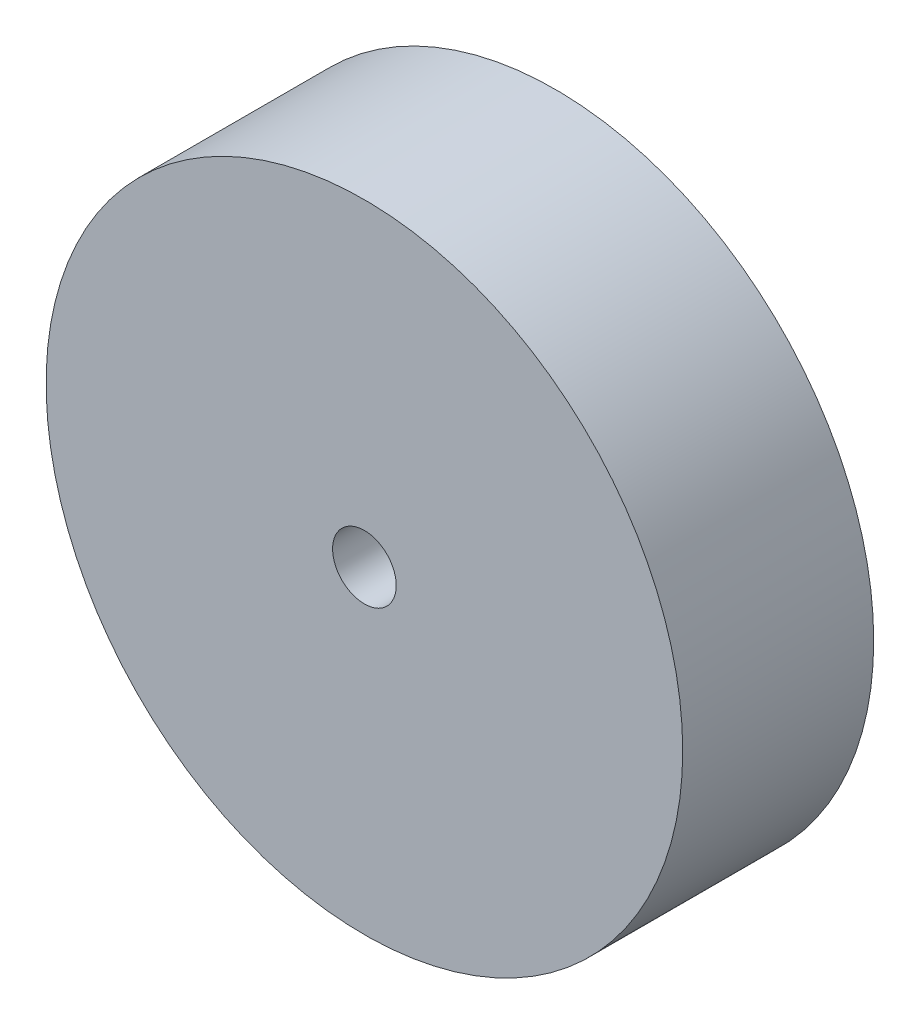
SolidWorks part; units mm, degrees
ref_plane "Front Plane" through (0, 0, 0) normal (0, 0, 1) x (1, 0, 0)
ref_plane "Top Plane" through (0, 0, 0) normal (0, 1, 0) x (1, 0, 0)
ref_plane "Right Plane" through (0, 0, 0) normal (1, 0, 0) x (0, 0, -1)
sketch "Sketch1" plane through (0, 0, 0) normal (0, 0, 1) x (1, 0, 0)
  circle A0 centre (0, 0) radius 25
  circle A1 centre (0, 0) radius 2.5
  dimension "D1" = 50
  dimension "D2" = 5
extrude "Boss-Extrude1" add sketch "Sketch1" along normal blind 15
